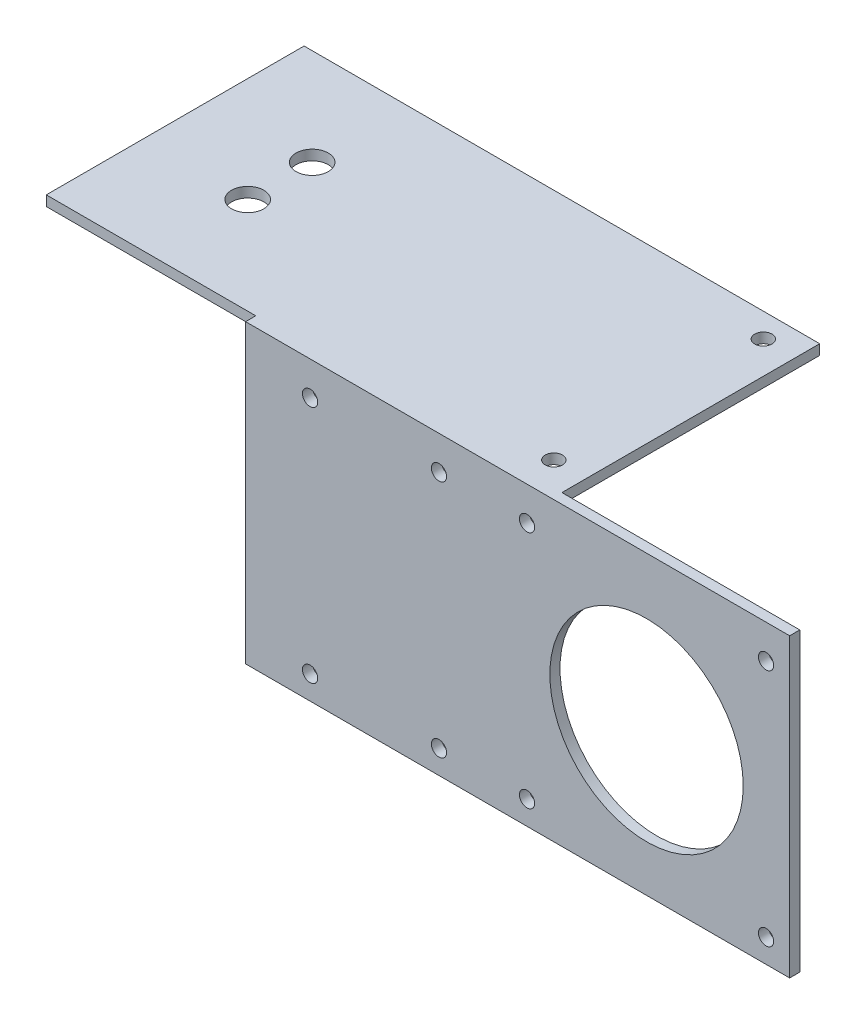
SolidWorks part; units mm, degrees
ref_plane "Front Plane" through (0, 0, 0) normal (0, 0, 1) x (1, 0, 0)
ref_plane "Top Plane" through (0, 0, 0) normal (0, 1, 0) x (1, 0, 0)
ref_plane "Right Plane" through (0, 0, 0) normal (1, 0, 0) x (0, 0, -1)
sketch "Sketch1" plane through (0, 0, 0) normal (0, 0, 1) x (1, 0, 0)
  line L0 (102.55, 51.75) -> (12.7, 51.75) construction
  line L1 (0, 58.4) -> (107.2, 58.4)
  line L2 (0, 58.4) -> (0, 0)
  line L3 (0, 0) -> (107.2, 0)
  line L4 (107.2, 58.4) -> (107.2, 0)
  line L5 (102.55, 51.75) -> (102.55, 4.65) construction
  line L6 (12.7, 51.75) -> (12.7, 4.65) construction
  line L7 (55.45, 4.65) -> (55.45, 51.75) construction
  line L8 (12.7, 4.65) -> (102.55, 4.65) construction
  line L9 (38.1, 51.75) -> (38.1, 4.65) construction
  line L10 (55.45, 51.75) -> (102.55, 4.65) construction
  line L11 (102.55, 51.75) -> (55.45, 4.65) construction
  circle A0 centre (102.55, 51.75) radius 1.5
  circle A1 centre (102.55, 4.65) radius 1.5
  circle A2 centre (55.45, 4.65) radius 1.5
  circle A3 centre (55.45, 51.75) radius 1.5
  circle A4 centre (12.7, 51.75) radius 1.5
  circle A5 centre (38.1, 51.75) radius 1.5
  circle A6 centre (12.7, 4.65) radius 1.5
  circle A7 centre (38.1, 4.65) radius 1.5
  circle A8 centre (79, 28.2) radius 19.05
  dimension "D3" = 3
  dimension "D10" = 38.1
  dimension "D1" = 58.4
  dimension "D2" = 107.2
  dimension "D4" = 47.1
  dimension "D5" = 47.1
  dimension "D6" = 4.65
  dimension "D7" = 25.4
  dimension "D8" = 4.65
  dimension "D9" = 12.7
extrude "Boss-Extrude1" add sketch "Sketch1" against normal blind 2
sketch "Sketch2" plane through (0, 0, -2) normal (0, 0, -1) x (-1, 0, 0)
  line L0 (0, 56.4) -> (41.275, 56.4)
  line L1 (0, 58.4) -> (0, 0) construction
  line L2 (0, 56.4) -> (-60.325, 56.4)
  line L3 (-60.325, 56.4) -> (-60.325, 58.4)
  line L4 (-107.2, 58.4) -> (0, 58.4) construction
  line L5 (-60.325, 58.4) -> (0, 58.4)
  line L6 (41.275, 56.4) -> (41.275, 58.4)
  line L7 (41.275, 58.4) -> (0, 58.4)
  dimension "D1" = 60.325
  dimension "D2" = 41.275
  dimension "D3" = 2
extrude "Boss-Extrude2" add sketch "Sketch2" along normal blind 50.8
sketch "Sketch3" plane through (0, 58.4, 0) normal (0, 1, 0) x (1, 0, 0)
  line L0 (53.975, 48.0375) -> (53.975, 6.7625) construction
  line L1 (-41.275, 52.8) -> (60.325, 52.8) construction
  line L2 (60.325, 52.8) -> (60.325, 2) construction
  line L3 (-20.6375, 33.75) -> (-20.6375, 21.05) construction
  line L4 (-41.275, 52.8) -> (60.325, 52.8) construction
  line L5 (-41.275, 52.8) -> (-41.275, 2) construction
  circle A0 centre (53.975, 48.0375) radius 1.7
  circle A1 centre (53.975, 6.7625) radius 1.7
  circle A2 centre (-20.6375, 33.75) radius 3.175
  circle A3 centre (-20.6375, 21.05) radius 3.175
  dimension "D1" = 3.4
  dimension "D2" = 41.275
  dimension "D5" = 6.35
  dimension "D6" = 6.35
  dimension "D3" = 4.7625
  dimension "D4" = 6.35
  dimension "D7" = 12.7
  dimension "D8" = 19.05
  dimension "D9" = 20.6375
extrude "Cut-Extrude1" cut sketch "Sketch3" against normal through all
